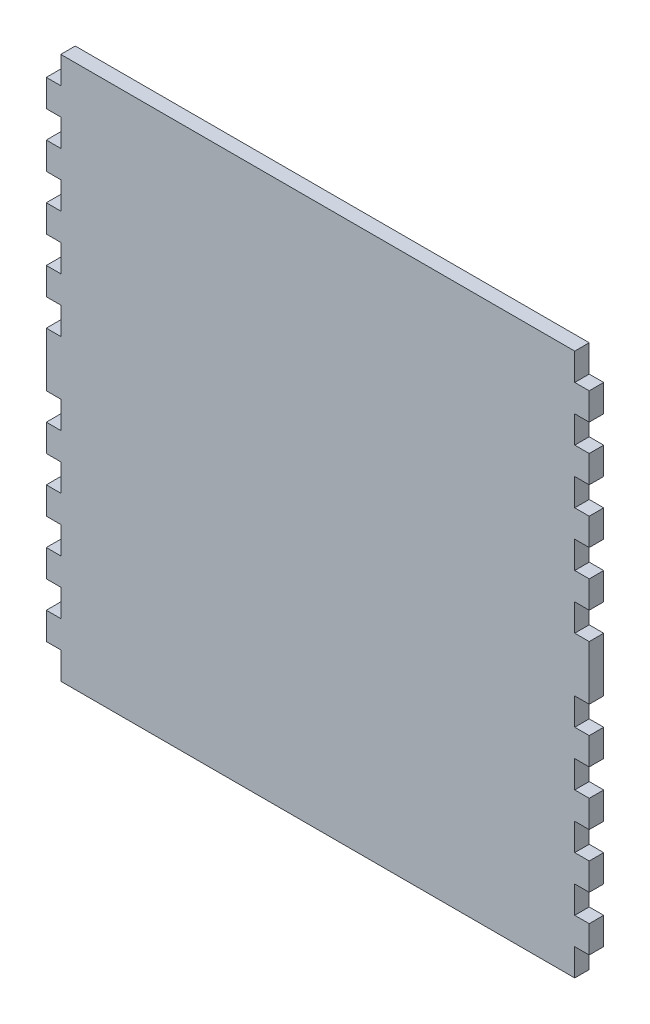
SolidWorks part; units mm, degrees
ref_plane "Plan de face" through (0, 0, 0) normal (0, 0, 1) x (1, 0, 0)
ref_plane "Plan de dessus" through (0, 0, 0) normal (0, 1, 0) x (1, 0, 0)
ref_plane "Plan de droite" through (0, 0, 0) normal (1, 0, 0) x (0, 0, -1)
sketch "Esquisse1" plane through (0, 0, 0) normal (0, 0, 1) x (1, 0, 0)
  line L1 (-150, -150) -> (150, -150)
  line L2 (-150, -150) -> (-150, 150)
  line L3 (-150, 150) -> (150, 150)
  line L4 (150, -150) -> (150, 150)
  line L5 (-150, -150) -> (150, 150) construction
  line L6 (-150, 150) -> (150, -150) construction
  point P0 (0, 0)
  dimension "D1" = 300
  dimension "D2" = 300
extrude "Boss.-Extru.1" add sketch "Esquisse1" along normal blind 8
sketch "Esquisse3" plane through (0, 0, 0) normal (0, 0, 1) x (1, 0, 0)
  line L0 (0, 0) -> (-192.143, 0) construction
  line L2 (-150, -15) -> (-142, -15)
  line L3 (-150, -15) -> (-150, -30)
  line L4 (-150, -30) -> (-142, -30)
  line L5 (-142, -15) -> (-142, -30)
  line L6 (-150, -45) -> (-150, -60)
  line L7 (-150, -45) -> (-142, -45)
  line L8 (-142, -45) -> (-142, -60)
  line L9 (-150, -60) -> (-142, -60)
  line L10 (-150, -75) -> (-150, -90)
  line L11 (-150, -75) -> (-142, -75)
  line L12 (-142, -75) -> (-142, -90)
  line L13 (-150, -90) -> (-142, -90)
  line L14 (-150, -105) -> (-150, -120)
  line L15 (-150, -105) -> (-142, -105)
  line L16 (-142, -105) -> (-142, -120)
  line L17 (-150, -120) -> (-142, -120)
  line L18 (-150, -135) -> (-150, -150)
  line L19 (-150, -135) -> (-142, -135)
  line L20 (-142, -135) -> (-142, -150)
  line L21 (-150, -150) -> (-142, -150)
  line L23 (-150, 60) -> (-142, 60)
  line L24 (-142, 45) -> (-142, 60)
  line L25 (-150, 45) -> (-150, 60)
  line L26 (-150, 135) -> (-142, 135)
  line L27 (-142, 135) -> (-142, 150)
  line L28 (-150, 150) -> (-142, 150)
  line L29 (-150, 135) -> (-150, 150)
  line L30 (-150, 105) -> (-142, 105)
  line L31 (-142, 105) -> (-142, 120)
  line L32 (-150, 120) -> (-142, 120)
  line L33 (-150, 105) -> (-150, 120)
  line L34 (-150, 75) -> (-142, 75)
  line L35 (-142, 75) -> (-142, 90)
  line L36 (-150, 90) -> (-142, 90)
  line L37 (-150, 75) -> (-150, 90)
  line L38 (-150, 45) -> (-142, 45)
  line L39 (-150, 30) -> (-142, 30)
  line L40 (-142, 15) -> (-142, 30)
  line L41 (-150, 15) -> (-142, 15)
  line L42 (-150, 15) -> (-150, 30)
  dimension "D1" = 15
  dimension "D2" = 8
  dimension "D3" = 15
  dimension "D4" = 5
extrude "Enlèv. mat.-Extru.4" cut sketch "Esquisse3" along normal through all
mirror "Symétrie1" about plane through (0, 0, 0) normal (1, 0, 0) of "Enlèv. mat.-Extru.4"
